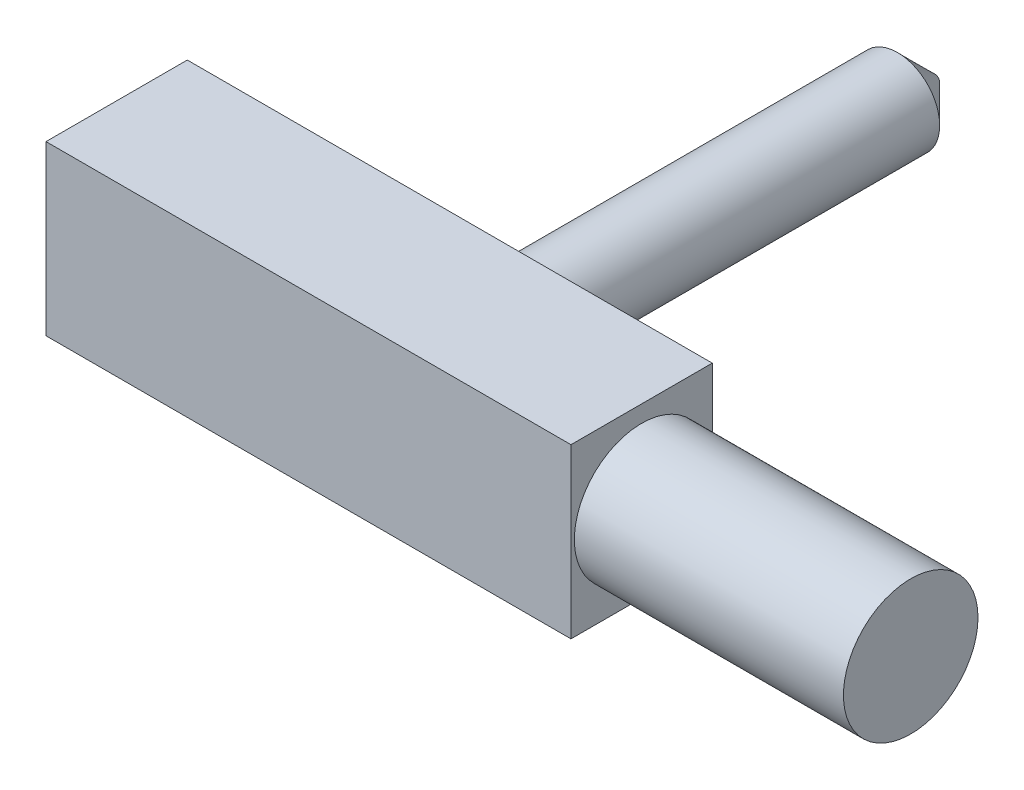
SolidWorks part; units mm, degrees
ref_plane "Front Plane" through (0, 0, 0) normal (0, 0, 1) x (1, 0, 0)
ref_plane "Top Plane" through (0, 0, 0) normal (0, 1, 0) x (1, 0, 0)
ref_plane "Right Plane" through (0, 0, 0) normal (1, 0, 0) x (0, 0, -1)
sketch "Sketch1" plane through (0, 0, 0) normal (0, 0, 1) x (1, 0, 0)
  line L1 (39.015, -12.5) -> (-39.015, -12.5)
  line L2 (39.015, -12.5) -> (39.015, 12.5)
  line L3 (39.015, 12.5) -> (-39.015, 12.5)
  line L4 (-39.015, -12.5) -> (-39.015, 12.5)
  point P0 (0, 0)
  dimension "D1" = 78.03
  dimension "D2" = 25
extrude "Boss-Extrude1" add sketch "Sketch1" against normal blind 21
sketch "Sketch2" plane through (39.015, 0, 0) normal (1, 0, 0) x (0, 0, -1)
  circle A0 centre (10.5, 0) radius 10
extrude "Boss-Extrude2" add sketch "Sketch2" along normal blind 40
sketch "Sketch4" plane through (0, 0, -21) normal (0, 0, -1) x (-1, 0, 0)
  circle A0 centre (-6.565, 0) radius 6.25
extrude "Boss-Extrude3" add sketch "Sketch4" along normal blind 65.56
chamfer "Chamfer1" distance 5.56 angle 45 1 edges at (0.315, 0, -86.56)
